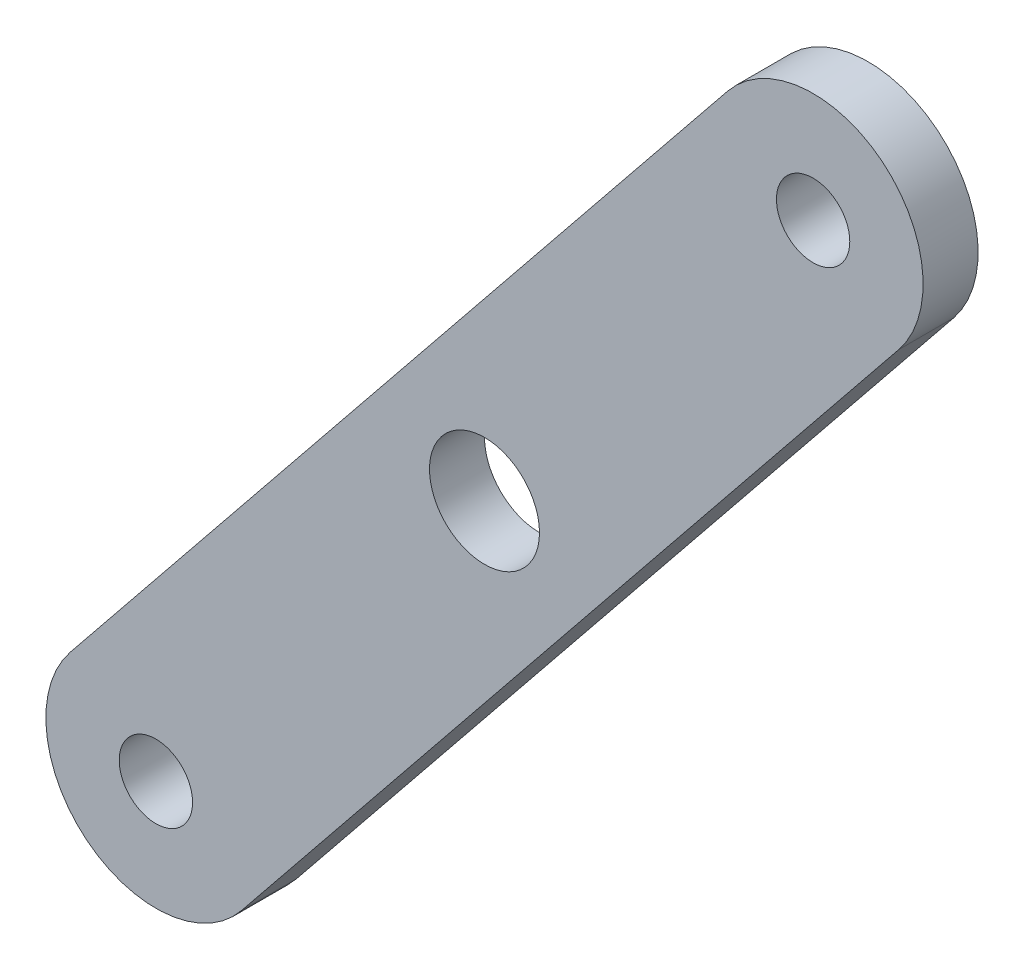
SolidWorks part; units mm, degrees
material "Zoltek Panex 33"
ref_plane "前视基准面" through (0, 0, 0) normal (0, 0, 1) x (1, 0, 0)
ref_plane "上视基准面" through (0, 0, 0) normal (0, 1, 0) x (1, 0, 0)
ref_plane "右视基准面" through (0, 0, 0) normal (1, 0, 0) x (0, 0, -1)
sketch "草图1" plane through (0, 0, 0) normal (0, 0, 1) x (1, 0, 0)
  line L0 (0, 0) -> (19.8618, 2.3475) construction
  line L1 (10.9, -8.7574) -> (28.8236, 13.4524) construction
  line L2 (8.5654, -6.8734) -> (26.489, 15.3365)
  line L3 (13.2346, -10.6415) -> (31.1582, 11.5684)
  arc A1 (8.5654, -6.8734) -> (13.2346, -10.6415) centre (10.9, -8.7574) ccw
  arc A2 (31.1582, 11.5684) -> (26.489, 15.3365) centre (28.8236, 13.4524) ccw
  circle A3 centre (28.8236, 13.4524) radius 1
  circle A4 centre (10.9, -8.7574) radius 1
  circle A5 centre (19.8618, 2.3475) radius 1.5
  point P6 (19.8618, 2.3475)
  dimension "D1" = 3
  dimension "D3" = 2
  dimension "D4" = 2
  dimension "D2" = 20
  dimension "D5" = 28.54
extrude "凸台-拉伸1" add sketch "草图1" along normal blind 1.5
